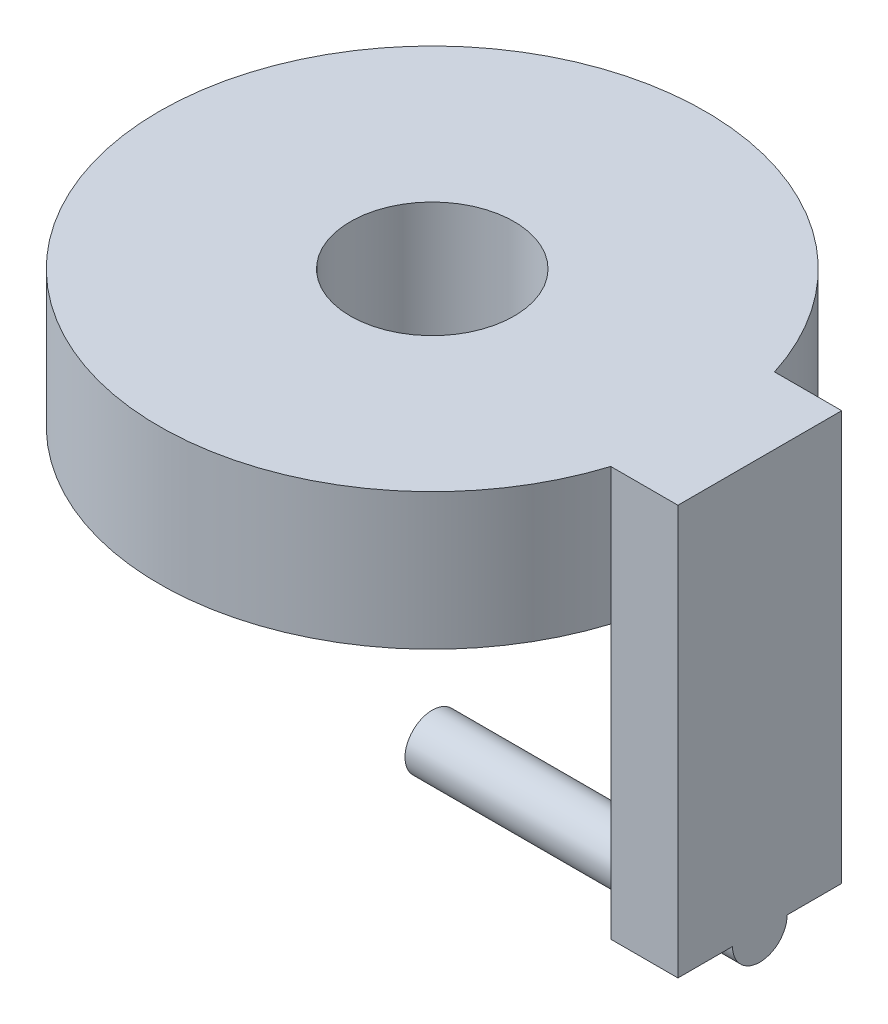
SolidWorks part; units mm, degrees
ref_plane "Front Plane" through (0, 0, 0) normal (0, 0, 1) x (1, 0, 0)
ref_plane "Top Plane" through (0, 0, 0) normal (0, 1, 0) x (1, 0, 0)
ref_plane "Right Plane" through (0, 0, 0) normal (1, 0, 0) x (0, 0, -1)
sketch "Sketch2" plane through (0, 0, 0) normal (0, 1, 0) x (1, 0, 0)
  circle A0 centre (0, 0) radius 15
  circle A1 centre (0, 0) radius 50
  dimension "D1" = 30
  dimension "D2" = 100
extrude "Boss-Extrude1" add sketch "Sketch2" along normal blind 25
sketch "Sketch3" plane through (0, 25, 0) normal (0, 1, 0) x (1, 0, 0)
  line L0 (50, 0) -> (60, 0) construction
  line L1 (47.697, 15) -> (60, 15)
  line L3 (47.697, -15) -> (60, -15)
  line L4 (60, 15) -> (60, -15)
  line L5 (50, 0) -> (60, -15) construction
  line L6 (50, 0) -> (60, 15) construction
  circle A0 centre (0, 0) radius 50 construction
  arc A1 (47.697, 15) -> (47.697, -15) centre (0, 0) cw
  point P3 (50, 0)
  dimension "D1" = 10
  dimension "D3" = 100
  dimension "D2" = 30
extrude "Boss-Extrude2" add sketch "Sketch3" against normal blind 75
sketch "Sketch4" plane through (60, 0, 0) normal (1, 0, 0) x (0, 0, -1)
  line L0 (-15, -50) -> (15, -50) construction
  circle A0 centre (0, -50) radius 5
  dimension "D1" = 10
extrude "Boss-Extrude3" add sketch "Sketch4" against normal blind 60
